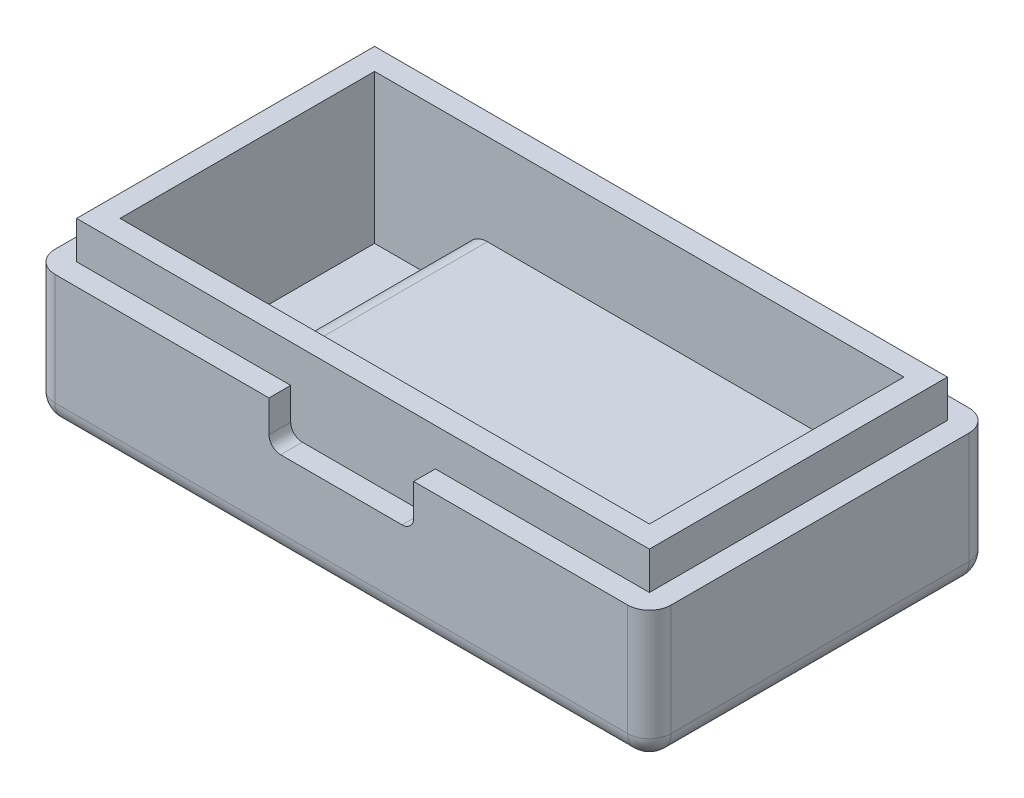
SolidWorks part; units mm, degrees
ref_plane "Front Plane" through (0, 0, 0) normal (0, 0, 1) x (1, 0, 0)
ref_plane "Top Plane" through (0, 0, 0) normal (0, 1, 0) x (1, 0, 0)
ref_plane "Right Plane" through (0, 0, 0) normal (1, 0, 0) x (0, 0, -1)
sketch "Sketch2" plane through (0, 0, 0) normal (0, 1, 0) x (1, 0, 0)
  line L1 (0, 0) -> (42.6, 0)
  line L2 (0, 0) -> (0, 23.6)
  line L3 (0, 23.6) -> (42.6, 23.6)
  line L4 (42.6, 0) -> (42.6, 23.6)
  dimension "D1" = 23.6
  dimension "D2" = 42.6
extrude "Boss-Extrude1" add sketch "Sketch2" along normal blind 11.8
sketch "Sketch4" plane through (0, 11.8, 0) normal (0, 1, 0) x (1, 0, 0)
  line L0 (21.3, 23.6) -> (21.3, 0) construction
  line L1 (42.6, 23.6) -> (0, 23.6) construction
  line L2 (0, 0) -> (42.6, 0) construction
  line L3 (9.3, 20.6) -> (9.3, 3)
  line L4 (9.3, 3) -> (39.6, 3)
  line L6 (9.3, 20.6) -> (39.6, 20.6)
  line L7 (39.6, 3) -> (39.6, 20.6)
  line L8 (3, 3) -> (39.6, 20.6) construction
  line L9 (3, 20.6) -> (39.6, 3) construction
  point P6 (21.3, 11.8)
  dimension "D1" = 17.6
  dimension "D2" = 36.6
sketch "Sketch5" plane through (0, 11.8, 0) normal (0, 1, 0) x (1, 0, 0)
  line L1 (9.3, 3) -> (3, 3)
  line L2 (9.3, 3) -> (9.3, 20.6)
  line L3 (9.3, 20.6) -> (3, 20.6)
  line L4 (3, 3) -> (3, 20.6)
extrude "Cut-Extrude2" cut sketch "Sketch4" against normal blind 6.3
extrude "Cut-Extrude3" cut sketch "Sketch5" against normal blind 10.3
sketch "Sketch6" plane through (0, 11.8, 0) normal (0, 1, 0) x (1, 0, 0)
  line L1 (0, 0) -> (42.6, 0)
  line L2 (0, 0) -> (0, 23.6)
  line L3 (0, 23.6) -> (42.6, 23.6)
  line L4 (42.6, 0) -> (42.6, 23.6)
  line L5 (1.5, 22.1) -> (41.1, 22.1)
  line L6 (1.5, 22.1) -> (1.5, 1.5)
  line L7 (1.5, 1.5) -> (41.1, 1.5)
  line L8 (41.1, 22.1) -> (41.1, 1.5)
  line L9 (3, 20.6) -> (39.6, 20.6) construction
  line L10 (3, 20.6) -> (3, 3) construction
  line L11 (3, 3) -> (39.6, 3) construction
  line L12 (39.6, 20.6) -> (39.6, 3) construction
  dimension "D1" = 1.5
  dimension "D2" = 1.5
  dimension "D3" = 1.5
  dimension "D4" = 1.5
extrude "Cut-Extrude4" cut sketch "Sketch6" against normal blind 2.6
fillet "Fillet1" radius 1.5 8 edges at (21.3, 0, -23.6) (21.3, 0, 0) (0, 4.6, 0) (0, 4.6, -23.6) (42.6, 4.6, -23.6) (42.6, 4.6, 0) (0, 0, -11.8) (42.6, 0, -11.8)
fillet "Fillet2" radius 1.5 1 edges at (9.3, 5.5, -11.8)
sketch "Sketch8" plane through (0, 0, 0) normal (0, 0, 1) x (1, 0, 0)
  line L0 (1.5, 9.2) -> (41.1, 9.2) construction
  line L1 (16.3, 9.2) -> (26.3, 9.2)
  line L2 (16.3, 9.2) -> (16.3, 7)
  line L3 (17.1, 6.2) -> (25.5, 6.2)
  line L4 (26.3, 9.2) -> (26.3, 7)
  line L5 (21.3, 6.2) -> (21.3, 1.5) construction
  line L6 (1.5, 1.5) -> (41.1, 1.5) construction
  arc A0 (26.3, 7) -> (25.5, 6.2) centre (25.5, 7) cw
  arc A1 (17.1, 6.2) -> (16.3, 7) centre (17.1, 7) cw
  point P14 (16.3, 6.2)
  dimension "D3" = 0.8
  dimension "D1" = 10
  dimension "D2" = 3
extrude "Cut-Extrude5" cut sketch "Sketch8" against normal up to surface (1.5 mm away) up to face at (21.3, 10.5, -1.5)
sketch "Sketch9" plane through (0, 0, -23.6) normal (0, 0, -1) x (-1, 0, 0)
  line L0 (-17.1, 6.2) -> (-25.5, 6.2) construction
  line L1 (-16.3, 9.2) -> (-26.3, 9.2)
  line L2 (-16.3, 9.2) -> (-16.3, 7)
  line L3 (-17.1, 6.2) -> (-25.5, 6.2)
  line L4 (-26.3, 9.2) -> (-26.3, 7)
  arc A0 (-16.3, 7) -> (-17.1, 6.2) centre (-17.1, 7) cw
  arc A1 (-25.5, 6.2) -> (-26.3, 7) centre (-25.5, 7) cw
  dimension "D1" = 0.8
extrude "Cut-Extrude6" cut sketch "Sketch9" against normal up to surface (1.5 mm away) up to face at (21.3, 10.5, -22.1)
